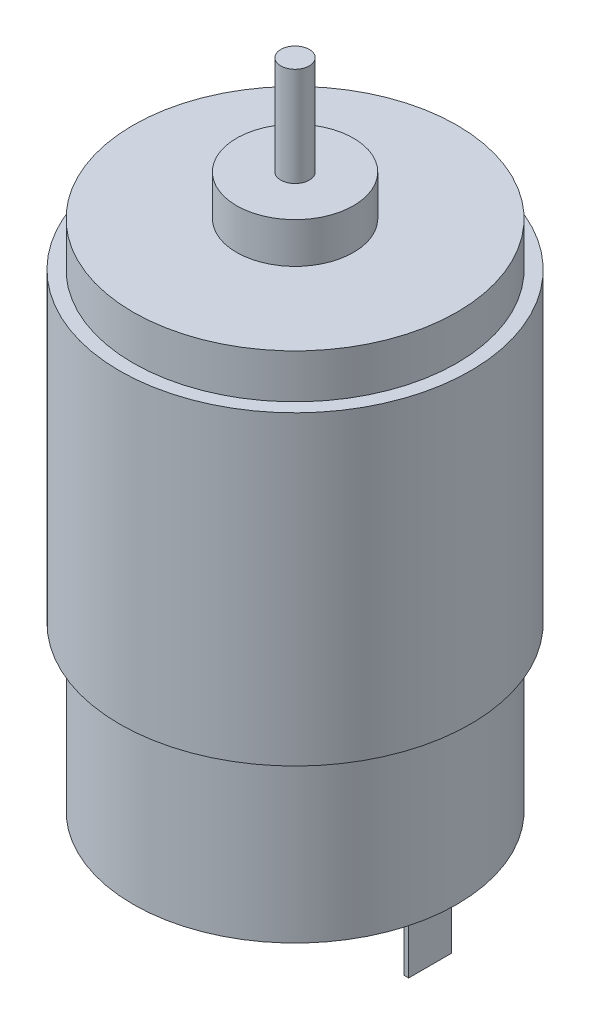
SolidWorks part; units mm, degrees
material "Motor Material"
ref_plane "Front Plane" through (0, 0, 0) normal (0, 0, 1) x (1, 0, 0)
ref_plane "Top Plane" through (0, 0, 0) normal (0, 1, 0) x (1, 0, 0)
ref_plane "Right Plane" through (0, 0, 0) normal (1, 0, 0) x (0, 0, -1)
sketch "Sketch1" plane through (0, 0, 0) normal (0, 1, 0) x (1, 0, 0)
  circle A0 centre (0, 0) radius 19.5
  circle A1 centre (0, 0) radius 18
  dimension "D1" = 39
  dimension "D2" = 36
extrude "Boss-Extrude1" add sketch "Sketch1" along normal blind 34
sketch "Sketch2" plane through (0, 34, 0) normal (0, 1, 0) x (1, 0, 0)
  circle A0 centre (0, 0) radius 18
  dimension "D1" = 36
extrude "Boss-Extrude2" add sketch "Sketch2" along normal blind 4.9 and the other way blind 52.1
sketch "Sketch3" plane through (0, 38.9, 0) normal (0, 1, 0) x (1, 0, 0)
  circle A0 centre (0, 0) radius 6.5
  dimension "D1" = 13
extrude "Boss-Extrude3" add sketch "Sketch3" along normal blind 4.5
sketch "Sketch4" plane through (0, 43.4, 0) normal (0, 1, 0) x (1, 0, 0)
  circle A0 centre (0, 0) radius 1.585
  dimension "D1" = 3.17
extrude "Boss-Extrude4" add sketch "Sketch4" along normal blind 11
sketch "Sketch5" plane through (0, -18.1, 0) normal (0, -1, 0) x (1, 0, 0)
  line L0 (0, 19.5) -> (0, -19.5) construction
  line L1 (14.5, 2.375) -> (15, 2.375)
  line L2 (14.5, 2.375) -> (14.5, -2.375)
  line L3 (14.5, -2.375) -> (15, -2.375)
  line L4 (15, 2.375) -> (15, -2.375)
  line L5 (-15, 2.375) -> (-15, -2.375)
  line L6 (-14.5, -2.375) -> (-15, -2.375)
  line L7 (-14.5, 2.375) -> (-14.5, -2.375)
  line L8 (-14.5, 2.375) -> (-15, 2.375)
  circle A0 centre (0, 0) radius 19.5 construction
  dimension "D1" = 14.5
  dimension "D2" = 4.75
  dimension "D3" = 0.5
  dimension "D4" = 2.375
extrude "Boss-Extrude5" add sketch "Sketch5" along normal blind 7.4
